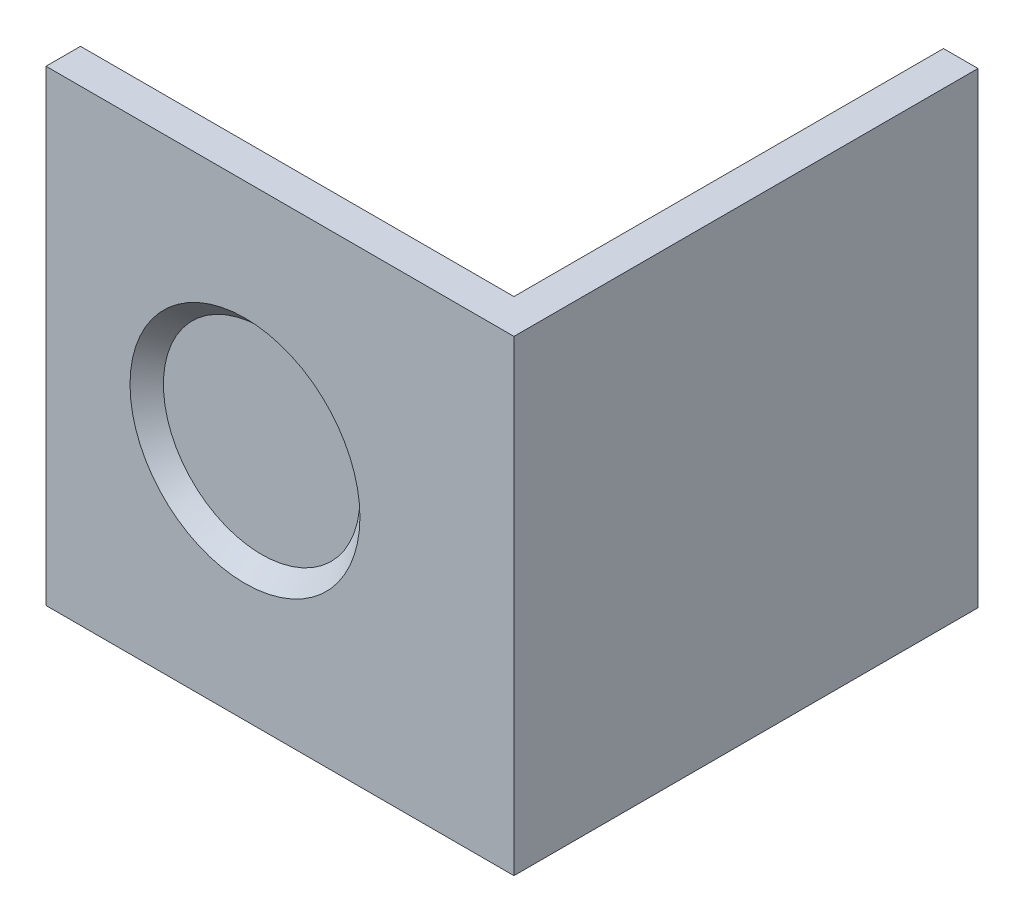
SolidWorks part; units mm, degrees
ref_plane "Front Plane" through (0, 0, 0) normal (0, 0, 1) x (1, 0, 0)
ref_plane "Top Plane" through (0, 0, 0) normal (0, 1, 0) x (1, 0, 0)
ref_plane "Right Plane" through (0, 0, 0) normal (1, 0, 0) x (0, 0, -1)
sketch "Sketch1" plane through (0, 0, 0) normal (0, 1, 0) x (1, 0, 0)
  line L0 (0, 0) -> (42.05, 0)
  line L1 (42.05, 0) -> (42.05, 41.7)
  line L2 (42.05, 41.7) -> (38.95, 41.7)
  line L3 (38.95, 41.7) -> (38.95, 3.1)
  line L4 (38.95, 3.1) -> (0, 3.1)
  line L5 (0, 3.1) -> (0, 0)
  dimension "D1" = 3.1
  dimension "D2" = 41.7
  dimension "D3" = 42.05
extrude "Boss-Extrude1" add sketch "Sketch1" along normal blind 41.97 contours L1 L2 L3 L4 L5 L0
sketch "Sketch2" plane through (42.05, 0, 0) normal (0, 0, -1) x (-1, 0, 0)
  line L0 (0, 41.97) -> (0, 0) construction
  line L1 (24.17, 20.985) -> (68.7901, 20.985)
  line L2 (0, 41.97) -> (68.7901, 20.985)
  line L3 (0, 0) -> (68.7901, 20.985)
  circle A0 centre (24.17, 20.985) radius 10.33
  dimension "D2" = 20.66
  dimension "D1" = 24.17
extrude "Cut-Extrude2" cut sketch "Sketch2" along normal blind 1.5 draft 45
